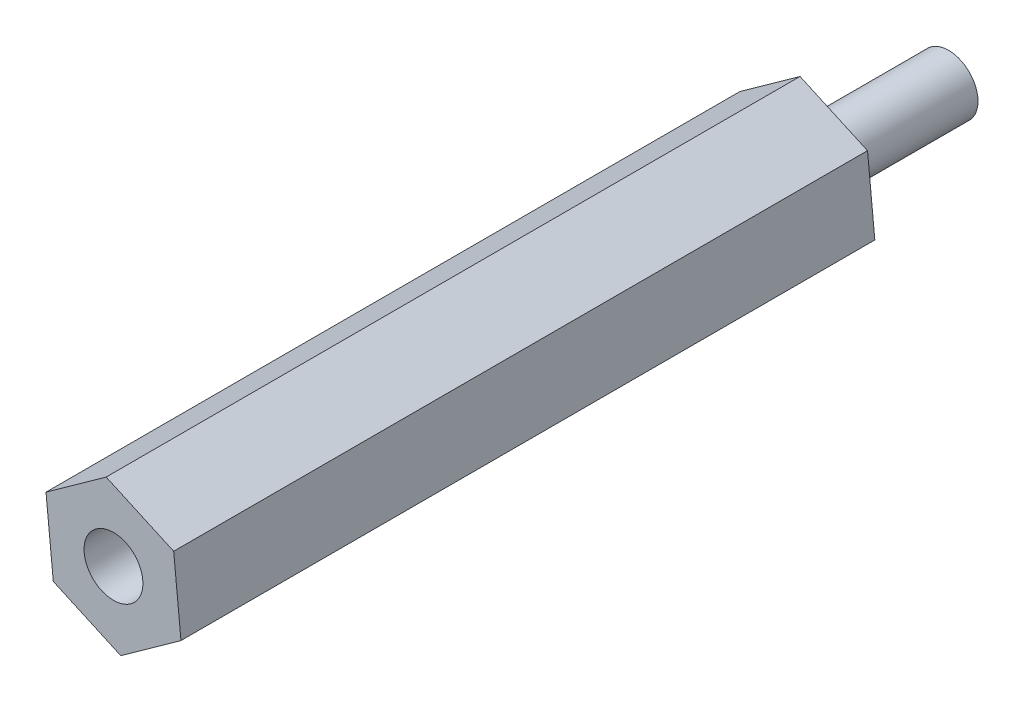
SolidWorks part; units mm, degrees
ref_plane "Front Plane" through (0, 0, 0) normal (0, 0, 1) x (1, 0, 0)
ref_plane "Top Plane" through (0, 0, 0) normal (0, 1, 0) x (1, 0, 0)
ref_plane "Right Plane" through (0, 0, 0) normal (1, 0, 0) x (0, 0, -1)
sketch "Sketch1" plane through (0, 0, 0) normal (0, 0, 1) x (1, 0, 0)
  line L1 (-2.5976, -1.8635) -> (0.315, -3.1813)
  line L2 (0.315, -3.1813) -> (2.9126, -1.3178)
  line L3 (2.9126, -1.3178) -> (2.5976, 1.8635)
  line L4 (2.5976, 1.8635) -> (-0.315, 3.1813)
  line L5 (-0.315, 3.1813) -> (-2.9126, 1.3178)
  line L6 (-2.9126, 1.3178) -> (-2.5976, -1.8635)
  circle A0 centre (0, 0) radius 2.7686 construction
extrude "Boss-Extrude1" add sketch "Sketch1" along normal blind 29.9466
sketch "Sketch2" plane through (0, 0, 29.9466) normal (0, 0, 1) x (1, 0, 0)
  circle A0 centre (0, 0) radius 1.27
extrude "Cut-Extrude1" cut sketch "Sketch2" against normal blind 24.8666
sketch "Sketch3" plane through (0, 0, 0) normal (0, 0, -1) x (-1, 0, 0)
  circle A0 centre (0, 0) radius 1.27
extrude "Boss-Extrude2" add sketch "Sketch3" along normal blind 6.096
